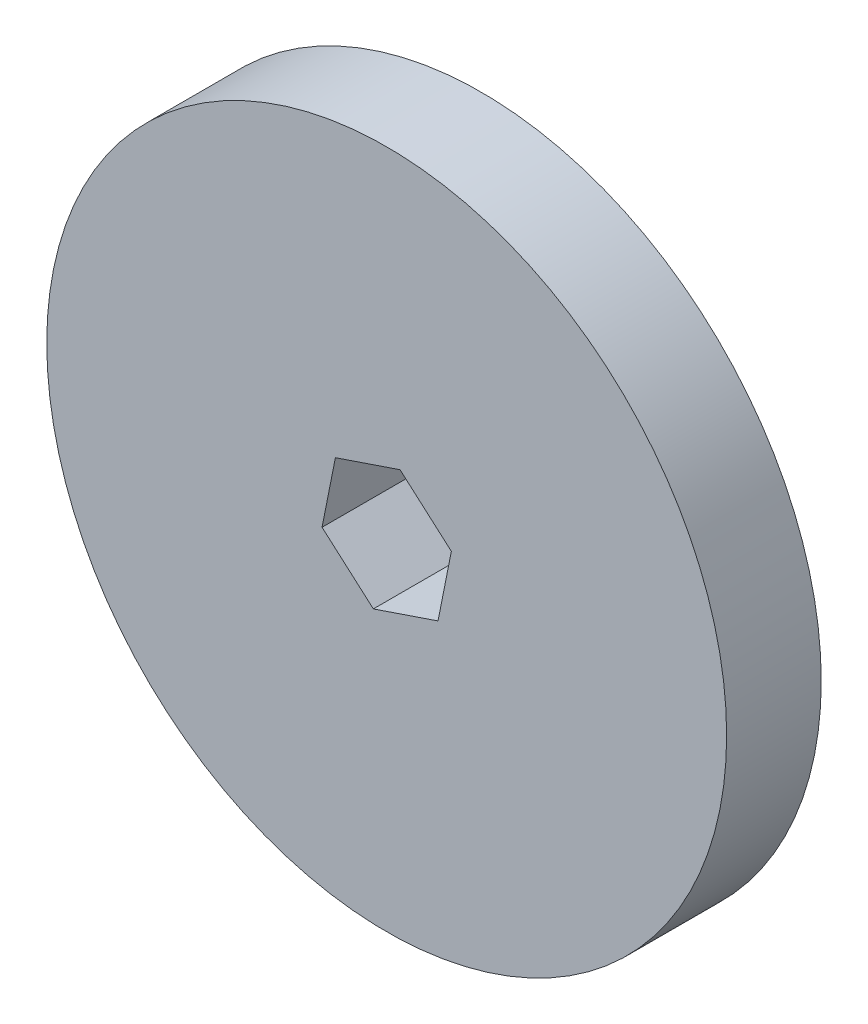
SolidWorks part; units mm, degrees
ref_plane "Front Plane" through (0, 0, 0) normal (0, 0, 1) x (1, 0, 0)
ref_plane "Top Plane" through (0, 0, 0) normal (0, 1, 0) x (1, 0, 0)
ref_plane "Right Plane" through (0, 0, 0) normal (1, 0, 0) x (0, 0, -1)
sketch "Sketch1" plane through (0, 0, 0) normal (0, 0, 1) x (1, 0, 0)
  circle A0 centre (0, 0) radius 36.5125
  dimension "D1" = 73.025
extrude "Boss-Extrude1" add sketch "Sketch1" along normal blind 10.16
sketch "Sketch2" plane through (0, 0, 10.16) normal (0, 0, 1) x (1, 0, 0)
  line L1 (6.9442, 2.354) -> (1.4335, 7.1909)
  line L2 (1.4335, 7.1909) -> (-5.5107, 4.8369)
  line L3 (-5.5107, 4.8369) -> (-6.9442, -2.354)
  line L4 (-6.9442, -2.354) -> (-1.4335, -7.1909)
  line L5 (-1.4335, -7.1909) -> (5.5107, -4.8369)
  line L6 (5.5107, -4.8369) -> (6.9442, 2.354)
  circle A0 centre (0, 0) radius 6.35 construction
extrude "Cut-Extrude1" cut sketch "Sketch2" against normal through all
